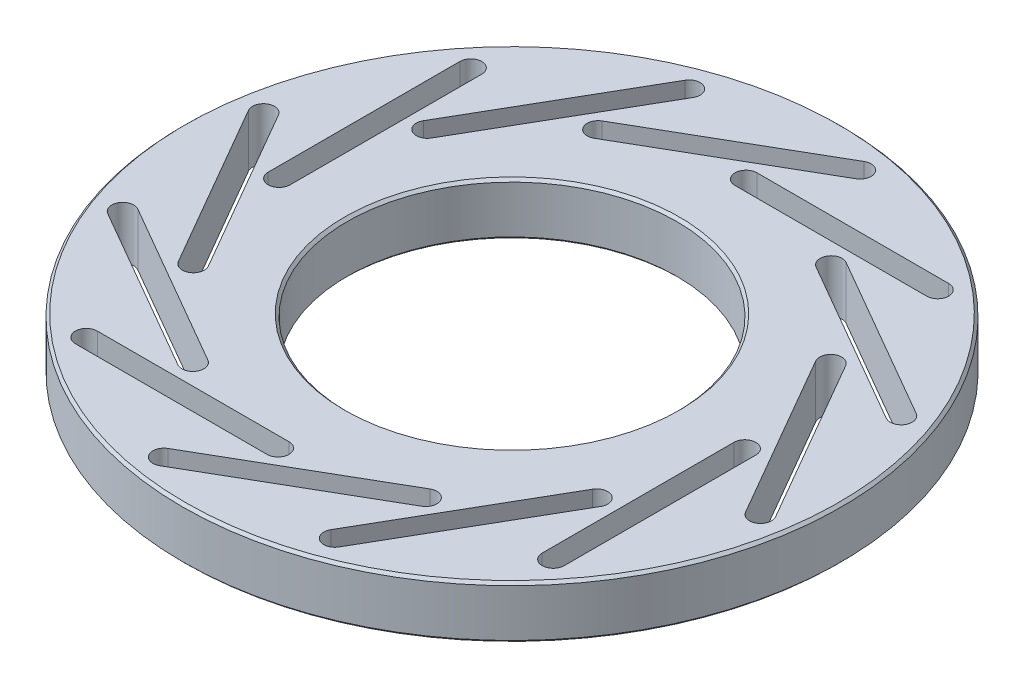
SolidWorks part; units mm, degrees
material "Plain Carbon Steel"
ref_plane "Front Plane" through (0, 0, 0) normal (0, 0, 1) x (1, 0, 0)
ref_plane "Top Plane" through (0, 0, 0) normal (0, 1, 0) x (1, 0, 0)
ref_plane "Right Plane" through (0, 0, 0) normal (1, 0, 0) x (0, 0, -1)
sketch "Sketch1" plane through (0, 0, 0) normal (0, 1, 0) x (1, 0, 0)
  line L0 (15.3567, 8.8181) -> (22.6275, -3.7754) construction
  line L1 (16.875, -14.5833) -> (16.875, -0.0417)
  line L2 (16.0784, 9.2347) -> (23.3492, -3.3587)
  line L3 (18.5417, -0.0417) -> (18.5417, -14.5833)
  line L4 (21.9058, -4.192) -> (14.635, 8.4014)
  line L5 (7.3225, -21.067) -> (14.5933, -8.4736)
  line L6 (16.0367, -9.3069) -> (8.7659, -21.9004)
  line L7 (-4.192, -21.9058) -> (8.4014, -14.635)
  line L8 (9.2347, -16.0784) -> (-3.3587, -23.3492)
  line L9 (-14.5833, -16.875) -> (-0.0417, -16.875)
  line L10 (-0.0417, -18.5417) -> (-14.5833, -18.5417)
  line L11 (-21.067, -7.3225) -> (-8.4736, -14.5933)
  line L12 (-9.3069, -16.0367) -> (-21.9004, -8.7659)
  line L13 (-21.9058, 4.192) -> (-14.635, -8.4014)
  line L14 (-16.0784, -9.2347) -> (-23.3492, 3.3587)
  line L15 (-16.875, 14.5833) -> (-16.875, 0.0417)
  line L16 (-18.5417, 0.0417) -> (-18.5417, 14.5833)
  line L17 (-7.3225, 21.067) -> (-14.5933, 8.4736)
  line L18 (-16.0367, 9.3069) -> (-8.7659, 21.9004)
  line L19 (4.192, 21.9058) -> (-8.4014, 14.635)
  line L20 (-9.2347, 16.0784) -> (3.3587, 23.3492)
  line L21 (14.5833, 16.875) -> (0.0417, 16.875)
  line L22 (0.0417, 18.5417) -> (14.5833, 18.5417)
  line L23 (21.067, 7.3225) -> (8.4736, 14.5933)
  line L24 (9.3069, 16.0367) -> (21.9004, 8.7659)
  arc A0 (16.0784, 9.2347) -> (14.635, 8.4014) centre (15.3567, 8.8181) ccw
  arc A1 (21.9058, -4.192) -> (23.3492, -3.3587) centre (22.6275, -3.7754) ccw
  circle A2 centre (0, 0) radius 25
  arc A3 (16.875, -14.5833) -> (18.5417, -14.5833) centre (17.7083, -14.5833) ccw
  arc A4 (18.5417, -0.0417) -> (16.875, -0.0417) centre (17.7083, -0.0417) ccw
  arc A5 (7.3225, -21.067) -> (8.7659, -21.9004) centre (8.0442, -21.4837) ccw
  arc A6 (16.0367, -9.3069) -> (14.5933, -8.4736) centre (15.315, -8.8903) ccw
  arc A7 (-4.192, -21.9058) -> (-3.3587, -23.3492) centre (-3.7754, -22.6275) ccw
  arc A8 (9.2347, -16.0784) -> (8.4014, -14.635) centre (8.8181, -15.3567) ccw
  arc A9 (-14.5833, -16.875) -> (-14.5833, -18.5417) centre (-14.5833, -17.7083) ccw
  arc A10 (-0.0417, -18.5417) -> (-0.0417, -16.875) centre (-0.0417, -17.7083) ccw
  arc A11 (-21.067, -7.3225) -> (-21.9004, -8.7659) centre (-21.4837, -8.0442) ccw
  arc A12 (-9.3069, -16.0367) -> (-8.4736, -14.5933) centre (-8.8903, -15.315) ccw
  arc A13 (-21.9058, 4.192) -> (-23.3492, 3.3587) centre (-22.6275, 3.7754) ccw
  arc A14 (-16.0784, -9.2347) -> (-14.635, -8.4014) centre (-15.3567, -8.8181) ccw
  arc A15 (-16.875, 14.5833) -> (-18.5417, 14.5833) centre (-17.7083, 14.5833) ccw
  arc A16 (-18.5417, 0.0417) -> (-16.875, 0.0417) centre (-17.7083, 0.0417) ccw
  arc A17 (-7.3225, 21.067) -> (-8.7659, 21.9004) centre (-8.0442, 21.4837) ccw
  arc A18 (-16.0367, 9.3069) -> (-14.5933, 8.4736) centre (-15.315, 8.8903) ccw
  arc A19 (4.192, 21.9058) -> (3.3587, 23.3492) centre (3.7754, 22.6275) ccw
  arc A20 (-9.2347, 16.0784) -> (-8.4014, 14.635) centre (-8.8181, 15.3567) ccw
  arc A21 (14.5833, 16.875) -> (14.5833, 18.5417) centre (14.5833, 17.7083) ccw
  arc A22 (0.0417, 18.5417) -> (0.0417, 16.875) centre (0.0417, 17.7083) ccw
  arc A23 (21.067, 7.3225) -> (21.9004, 8.7659) centre (21.4837, 8.0442) ccw
  arc A24 (9.3069, 16.0367) -> (8.4736, 14.5933) centre (8.8903, 15.315) ccw
  circle A25 centre (0, 0) radius 12.5
  point P74 (0, 0)
  dimension "D1" = 50
  dimension "D2" = 25
extrude "Boss-Extrude1" add sketch "Sketch1" along normal blind 4
sketch "Sketch6" plane through (0, 4, 0) normal (0, 1, 0) x (1, 0, 0)
  line L0 (0.0417, 17.7083) -> (-0.025, 0) construction
  line L1 (0, 0.025) -> (-0.0125, 0.0217) construction
  line L2 (-0.0125, 0.0217) -> (-0.0217, 0.0125) construction
  line L3 (-0.0217, 0.0125) -> (-0.025, 0) construction
  line L4 (-0.025, 0) -> (-0.0217, -0.0125) construction
  line L5 (-0.0217, -0.0125) -> (-0.0125, -0.0217) construction
  line L6 (-0.0125, -0.0217) -> (0, -0.025) construction
  line L7 (0, -0.025) -> (0.0125, -0.0217) construction
  line L8 (0.0125, -0.0217) -> (0.0217, -0.0125) construction
  line L9 (0.0217, -0.0125) -> (0.025, 0) construction
  line L10 (0.025, 0) -> (0.0217, 0.0125) construction
  line L11 (0.0217, 0.0125) -> (0.0125, 0.0217) construction
  line L12 (0.0125, 0.0217) -> (0, 0.025) construction
  line L13 (10.4759, 14.3916) -> (7.8416, 9.8681)
  line L14 (-0.025, 0) -> (-0.0216, 0.0126)
  line L15 (15.3567, 8.8181) -> (-0.0125, 0.0217) construction
  line L16 (7.8416, 9.8681) -> (7.7885, 9.777)
  line L18 (-0.0216, 0.0126) -> (3.2574, 12.0681)
  line L19 (-0.0217, 0.0125) -> (8.855, 8.8226)
  line L20 (7.3046, 16.2385) -> (4.6685, 11.7122)
  line L21 (4.6685, 11.7122) -> (4.6134, 11.6175)
  line L22 (-0.021, 0.0135) -> (-0.0216, 0.0126) construction
  line L26 (8.1687, 15.7353) -> (5.5327, 11.2089) construction
  line L27 (9.6118, 14.8948) -> (6.9774, 10.3714) construction
  circle A0 centre (0, 0) radius 0.025 construction
  circle A1 centre (0, 0) radius 0.0241 construction
  circle A2 centre (0.0417, 17.7083) radius 0.8333 construction
  arc A3 (9.6118, 14.8948) -> (8.1687, 15.7353) centre (8.8903, 15.315) ccw
  circle A4 centre (15.3567, 8.8181) radius 0.8333 construction
  arc A5 (4.6134, 11.6175) -> (3.2574, 12.0681) centre (0, 0) ccw
  arc A6 (10.4759, 14.3916) -> (7.3046, 16.2385) centre (8.8903, 15.315) ccw
  circle A7 centre (8.8903, 15.315) radius 0.835
  arc A8 (8.855, 8.8226) -> (7.7885, 9.777) centre (0, 0) ccw
  circle A9 centre (0, 0) radius 0.05 construction
  dimension "D1" = 0.05
  dimension "D4" = 0.1
  dimension "D2" = 1
  dimension "D3" = 15
chamfer "Chamfer1" distance 0.2 angle 45 4 edges at (0, 4, 12.5) (0, 0, 12.5) (0, 4, 25) (0, 0, 25)
